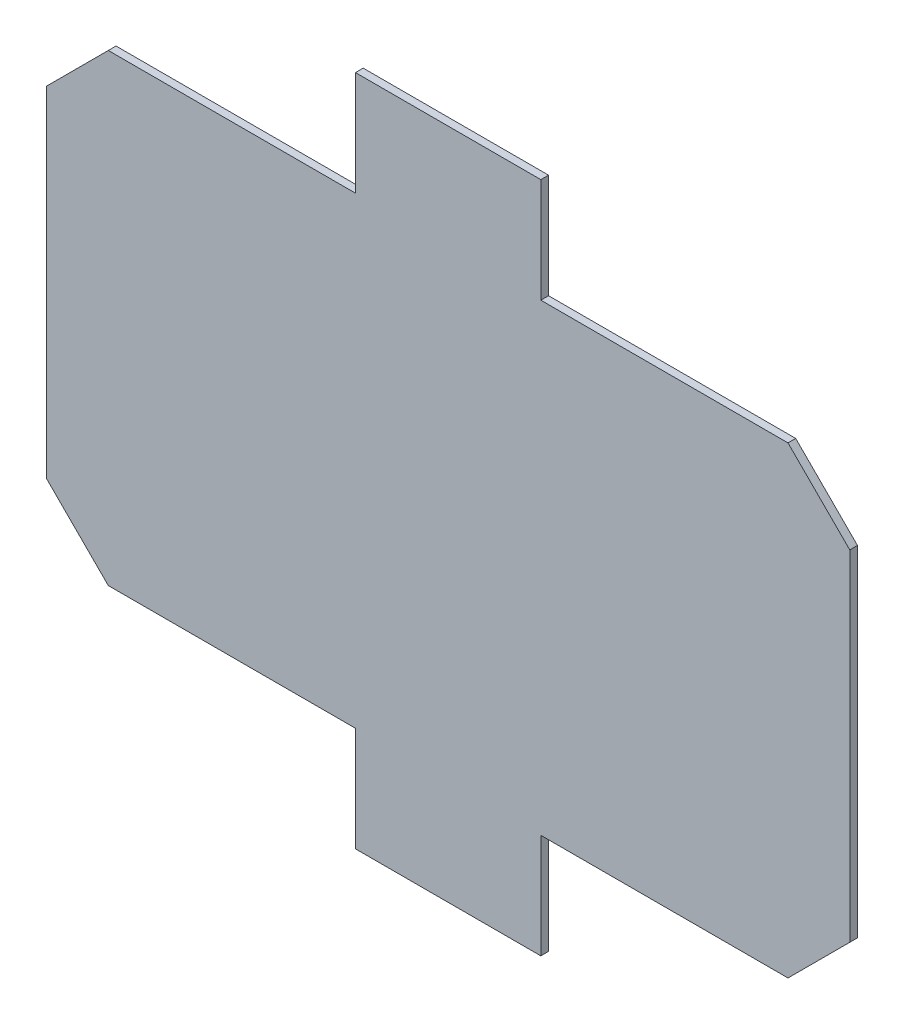
SolidWorks part; units mm, degrees
ref_plane "Front Plane" through (0, 0, 0) normal (0, 0, 1) x (1, 0, 0)
ref_plane "Top Plane" through (0, 0, 0) normal (0, 1, 0) x (1, 0, 0)
ref_plane "Right Plane" through (0, 0, 0) normal (1, 0, 0) x (0, 0, -1)
sketch "Sketch1" plane through (0, 0, 0) normal (0, 0, 1) x (1, 0, 0)
  line L0 (-100, 392.6) -> (100, 392.6) construction
  line L1 (-60, -42.6) -> (60, -42.6)
  line L2 (-60, -42.6) -> (-60, 392.6)
  line L3 (-60, 392.6) -> (60, 392.6)
  line L4 (60, -42.6) -> (60, 392.6)
  line L5 (-60, -42.6) -> (60, 392.6) construction
  line L6 (-60, 392.6) -> (60, -42.6) construction
  line L7 (100, -42.6) -> (-100, -42.6) construction
  line L8 (60, 392.6) -> (60, 325) construction
  line L9 (-60, 392.6) -> (-60, 325) construction
  line L11 (-260, 25) -> (260, 25)
  line L12 (-260, 25) -> (-260, 325)
  line L13 (-260, 325) -> (260, 325)
  line L14 (260, 25) -> (260, 325)
  line L15 (-260, 25) -> (260, 325) construction
  line L16 (-260, 325) -> (260, 25) construction
  point P0 (0, 175)
  point P13 (0, 175)
  dimension "D1" = 520
  dimension "D2" = 300
extrude "Boss-Extrude1" add sketch "Sketch1" along normal blind 5 contours L2 L13 L4 L3 | L13 L12 L11 L2 | L13 L2 L11 L4 | L11 L14 L13 L4 | L11 L2 L1 L4
chamfer "Chamfer1" distance 40 angle 45 4 edges at (260, 25, 2.5) (260, 325, 2.5) (-260, 325, 2.5) (-260, 25, 2.5)
